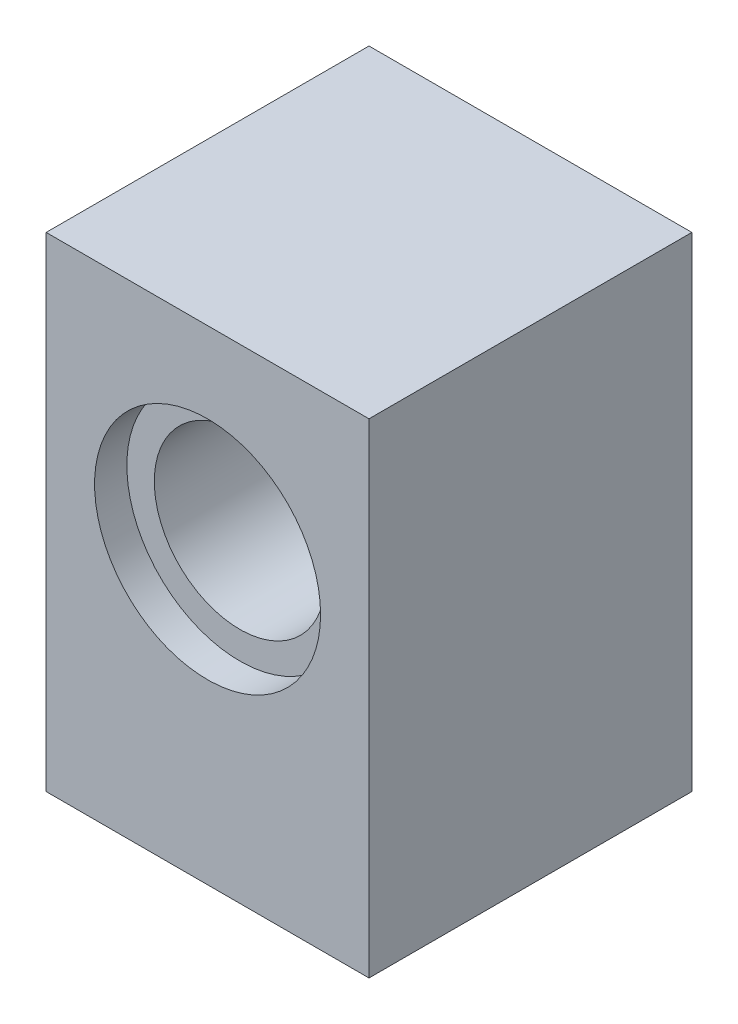
SolidWorks part; units mm, degrees
ref_plane "Front Plane" through (0, 0, 0) normal (0, 0, 1) x (1, 0, 0)
ref_plane "Top Plane" through (0, 0, 0) normal (0, 1, 0) x (1, 0, 0)
ref_plane "Right Plane" through (0, 0, 0) normal (1, 0, 0) x (0, 0, -1)
sketch "Sketch1" plane through (0, 0, 0) normal (0, 1, 0) x (1, 0, 0)
  line L1 (0, 0) -> (10, 0)
  line L2 (0, 0) -> (0, 10)
  line L3 (0, 10) -> (10, 10)
  line L4 (10, 0) -> (10, 10)
  dimension "D1" = 10
  dimension "D2" = 10
extrude "Boss-Extrude1" add sketch "Sketch1" along normal blind 15
sketch "Sketch2" plane through (0, 0, 0) normal (0, 0, 1) x (1, 0, 0)
  line L0 (0, 0) -> (10, 0) construction
  line L1 (0, 15) -> (0, 0) construction
  circle A0 centre (5, 9) radius 3.5
  dimension "D3" = 7
  dimension "D1" = 9
  dimension "D2" = 5
extrude "Cut-Extrude1" cut sketch "Sketch2" against normal blind 1
sketch "Sketch3" plane through (0, 0, -1) normal (0, 0, 1) x (1, 0, 0)
  circle A0 centre (5, 9) radius 2.65
  circle A1 centre (5, 9) radius 3.5 construction
  dimension "D1" = 5.3
  dimension "D2" = 0
extrude "Cut-Extrude2" cut sketch "Sketch3" against normal blind 7.9
sketch "Sketch4" plane through (0, 0, -8.9) normal (0, 0, 1) x (1, 0, 0)
  circle A0 centre (5, 9) radius 0.75
  circle A2 centre (5, 9) radius 2.65 construction
  dimension "D1" = 1.5
  dimension "D2" = 0
extrude "Cut-Extrude3" cut sketch "Sketch4" against normal through all
